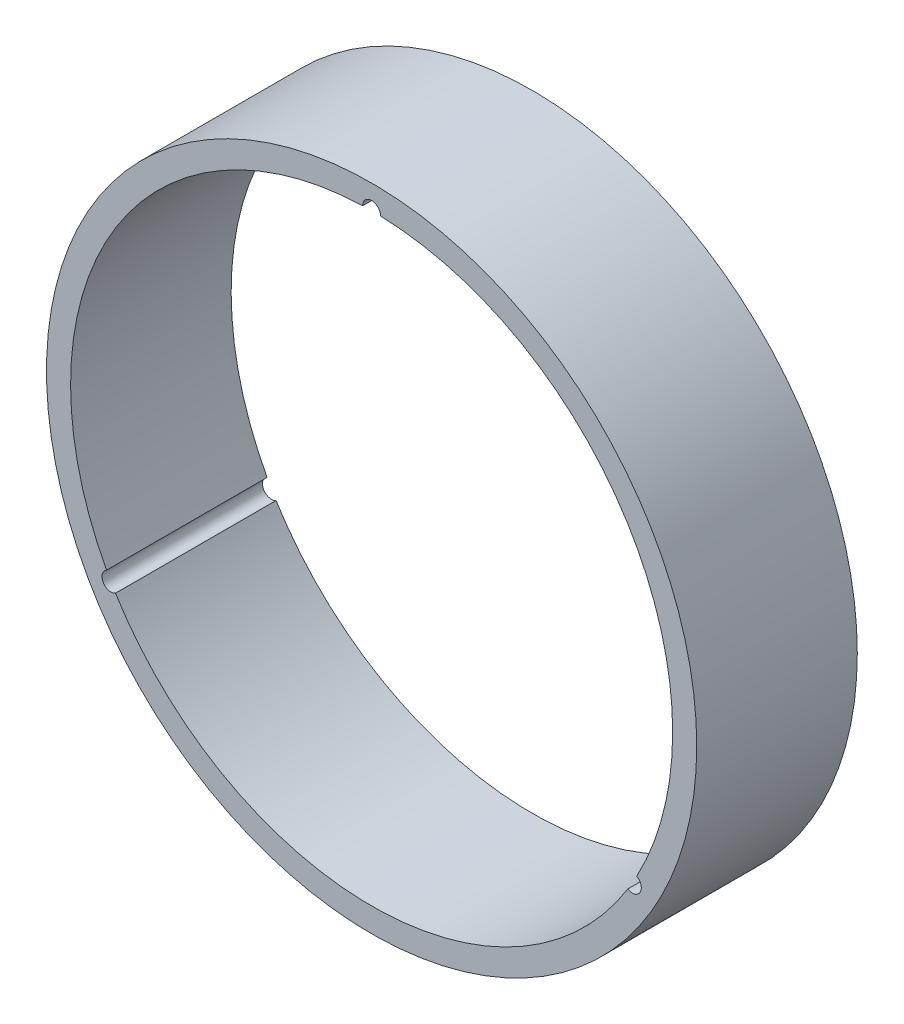
SolidWorks part; units mm, degrees
ref_plane "Front Plane" through (0, 0, 0) normal (0, 0, 1) x (1, 0, 0)
ref_plane "Top Plane" through (0, 0, 0) normal (0, 1, 0) x (1, 0, 0)
ref_plane "Right Plane" through (0, 0, 0) normal (1, 0, 0) x (0, 0, -1)
sketch "Sketch1" plane through (0, 0, 0) normal (0, 0, 1) x (1, 0, 0)
  line L0 (0, 75) -> (0, 0) construction
  line L1 (0, 0) -> (75, 0) construction
  circle A0 centre (0, 0) radius 75
  circle A1 centre (0, 0) radius 81
  circle A2 centre (0, 75) radius 2.2319
  circle A3 centre (64.9519, -37.5) radius 2.2319
  circle A4 centre (-64.9519, -37.5) radius 2.2319
  point P13 (0, 0)
  dimension "D1" = 150
  dimension "D2" = 6
  dimension "D3" = 90
  dimension "D4" = 3
extrude "Boss-Extrude1" add sketch "Sketch1" along normal blind 40 contours A1 A4 A0 A2 A3
